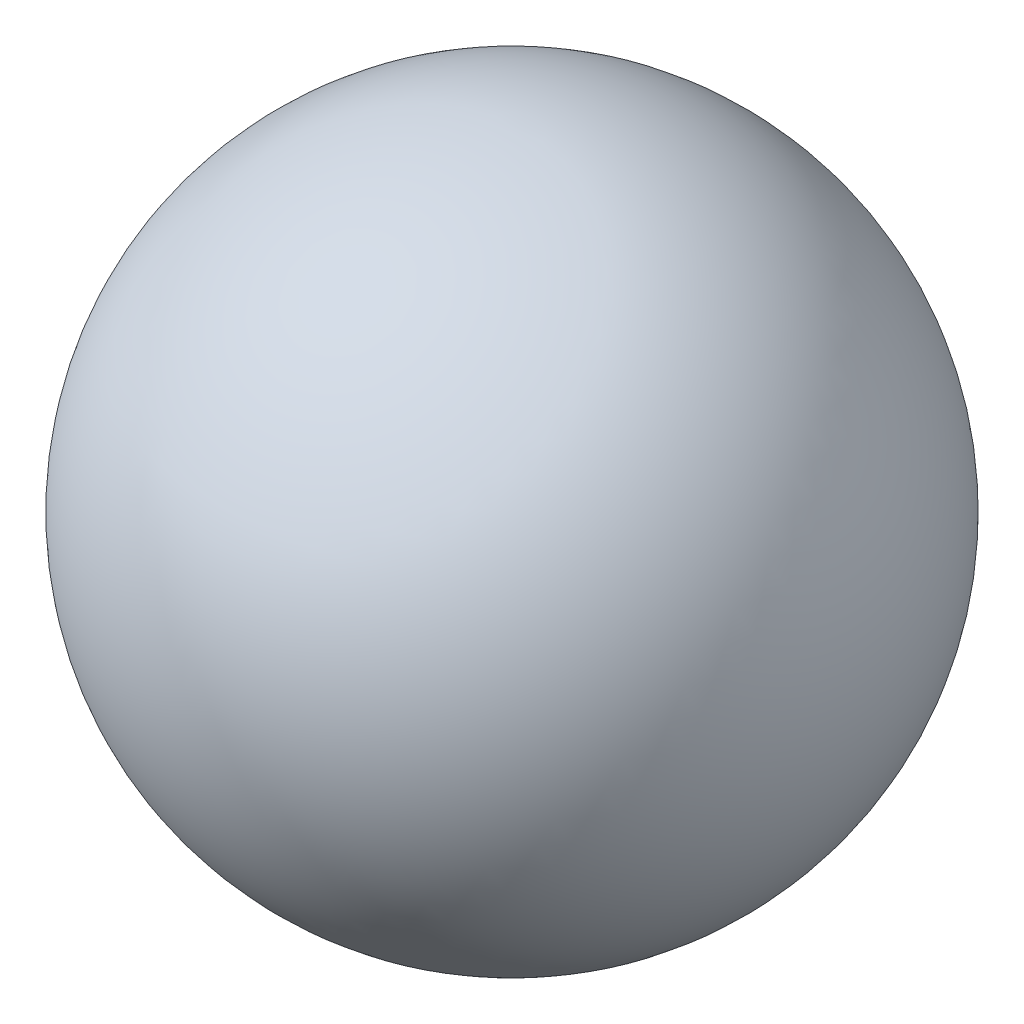
SolidWorks part; units mm, degrees
ref_plane "Alzado" through (0, 0, 0) normal (0, 0, 1) x (1, 0, 0)
ref_plane "Planta" through (0, 0, 0) normal (0, 1, 0) x (1, 0, 0)
ref_plane "Vista lateral" through (0, 0, 0) normal (1, 0, 0) x (0, 0, -1)
sketch "Croquis2" plane through (0, 0, 0) normal (1, 0, 0) x (0, 0, -1)
  line L0 (0, 74) -> (0, 0) construction
  line L2 (0, 0) -> (0, 74)
  arc A0 (0, 0) -> (0, 74) centre (0, 37) cw
  dimension "D1" = 37
revolve "Revolución1" add sketch "Croquis2" angle 360 about L0
